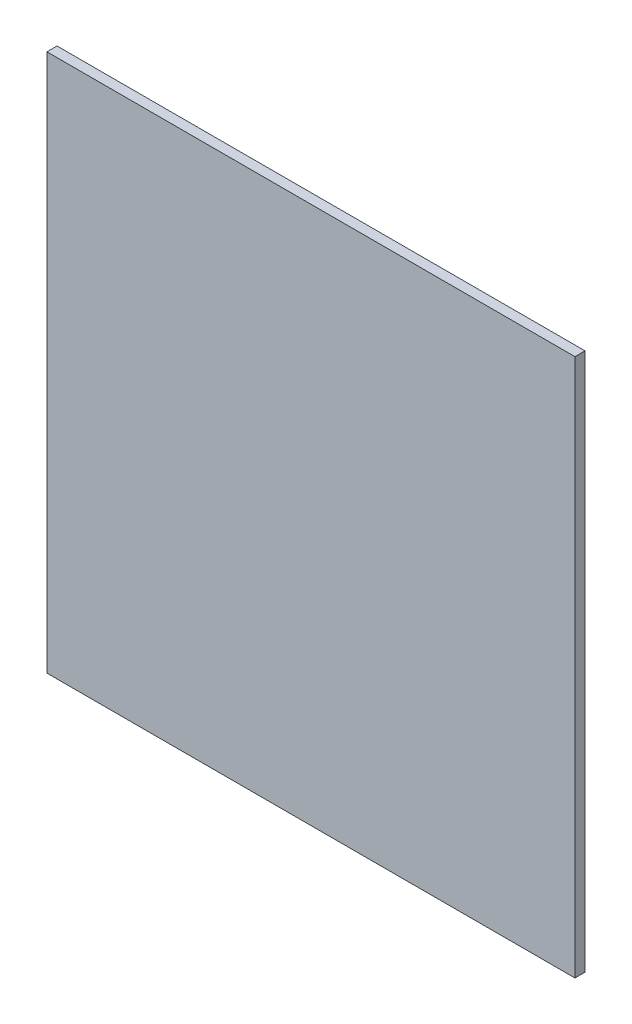
SolidWorks part; units mm, degrees
ref_plane "Front Plane" through (0, 0, 0) normal (0, 0, 1) x (1, 0, 0)
ref_plane "Top Plane" through (0, 0, 0) normal (0, 1, 0) x (1, 0, 0)
ref_plane "Right Plane" through (0, 0, 0) normal (1, 0, 0) x (0, 0, -1)
sketch "Sketch1" plane through (0, 0, 0) normal (0, 0, 1) x (1, 0, 0)
  line L1 (0, 0) -> (78.5, 0)
  line L2 (0, 0) -> (0, 80)
  line L3 (0, 80) -> (78.5, 80)
  line L4 (78.5, 0) -> (78.5, 80)
  dimension "D1" = 80
  dimension "D2" = 78.5
extrude "Boss-Extrude1" add sketch "Sketch1" along normal blind 1.5
